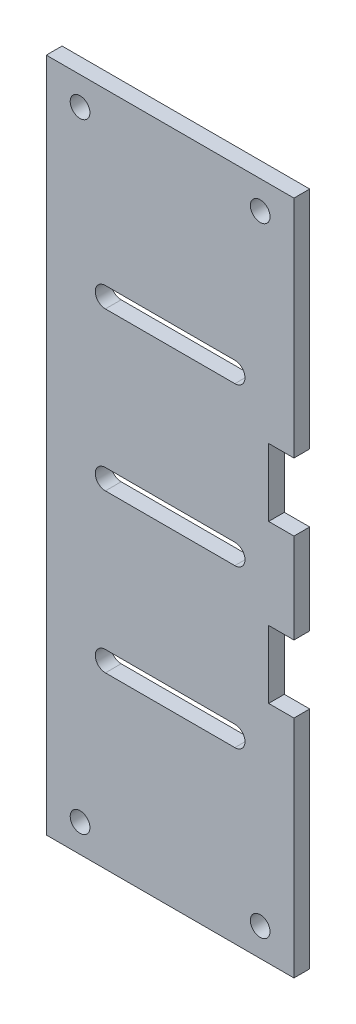
SolidWorks part; units mm, degrees
ref_plane "Front Plane" through (0, 0, 0) normal (0, 0, 1) x (1, 0, 0)
ref_plane "Top Plane" through (0, 0, 0) normal (0, 1, 0) x (1, 0, 0)
ref_plane "Right Plane" through (0, 0, 0) normal (1, 0, 0) x (0, 0, -1)
sketch "Cover with clamp hardware clearances profile" plane through (0, 0, 0) normal (0, 0, 1) x (1, 0, 0)
  line L0 (-22, -60) -> (22, -60)
  line L1 (22, -60) -> (22, -20)
  line L2 (22, -20) -> (17.5, -20)
  line L3 (17.5, -20) -> (17.5, -8)
  line L4 (17.5, -8) -> (22, -8)
  line L5 (22, -8) -> (22, 8)
  line L6 (22, 8) -> (17.5, 8)
  line L7 (17.5, 8) -> (17.5, 20)
  line L8 (17.5, 20) -> (22, 20)
  line L9 (22, 20) -> (22, 60)
  line L10 (22, 60) -> (-22, 60)
  line L11 (-22, 60) -> (-22, -60)
  line L12 (-11.5, -29.8) -> (11.5, -29.8)
  line L13 (11.5, -26.2) -> (-11.5, -26.2)
  line L14 (-11.5, -1.8) -> (11.5, -1.8)
  line L15 (11.5, 1.8) -> (-11.5, 1.8)
  line L16 (-11.5, 26.2) -> (11.5, 26.2)
  line L17 (11.5, 29.8) -> (-11.5, 29.8)
  circle A0 centre (-16, -55) radius 1.75
  circle A1 centre (-16, 55) radius 1.75
  circle A2 centre (16, -55) radius 1.75
  circle A3 centre (16, 55) radius 1.75
  arc A4 (11.5, -29.8) -> (11.5, -26.2) centre (11.5, -28) ccw
  arc A5 (-11.5, -26.2) -> (-11.5, -29.8) centre (-11.5, -28) ccw
  arc A6 (11.5, -1.8) -> (11.5, 1.8) centre (11.5, 0) ccw
  arc A7 (-11.5, 1.8) -> (-11.5, -1.8) centre (-11.5, 0) ccw
  arc A8 (11.5, 26.2) -> (11.5, 29.8) centre (11.5, 28) ccw
  arc A9 (-11.5, 29.8) -> (-11.5, 26.2) centre (-11.5, 28) ccw
extrude "Cover with clamp hardware clearances" add sketch "Cover with clamp hardware clearances profile" along normal blind 2.8
